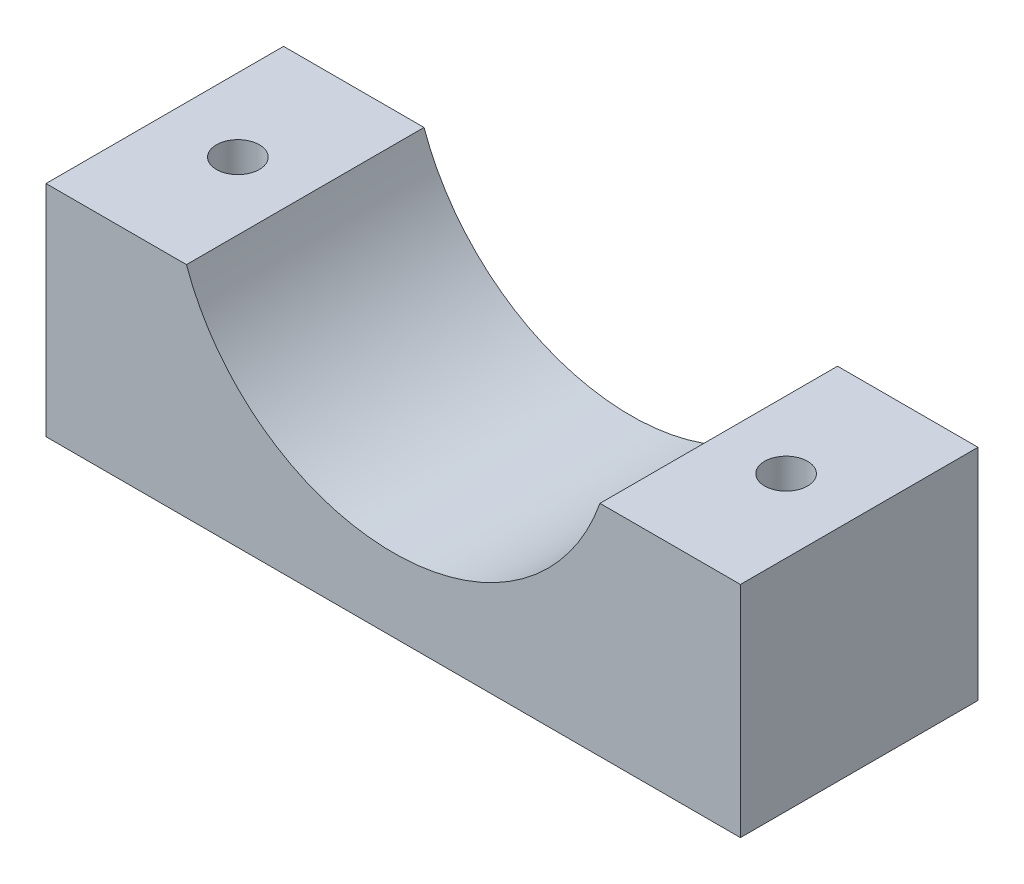
SolidWorks part; units mm, degrees
ref_plane "Front Plane" through (0, 0, 0) normal (0, 0, 1) x (1, 0, 0)
ref_plane "Top Plane" through (0, 0, 0) normal (0, 1, 0) x (1, 0, 0)
ref_plane "Right Plane" through (0, 0, 0) normal (1, 0, 0) x (0, 0, -1)
sketch "Sketch1" plane through (0, 0, 0) normal (0, 1, 0) x (1, 0, 0)
  line L1 (0, 0) -> (38, 0)
  line L2 (0, 0) -> (0, 13)
  line L3 (0, 13) -> (38, 13)
  line L4 (38, 0) -> (38, 13)
  dimension "D1" = 38
  dimension "D2" = 13
extrude "Boss-Extrude1" add sketch "Sketch1" along normal blind 12
sketch "Sketch2" plane through (0, 0, 0) normal (0, 0, 1) x (1, 0, 0)
  line L0 (0, 0) -> (38, 0) construction
  line L1 (0, 0) -> (38, 0) construction
  line L2 (0, 12) -> (0, 0) construction
  circle A0 centre (19, 16) radius 12
  dimension "D1" = 24
  dimension "D2" = 16
  dimension "D3" = 19
extrude "Cut-Extrude1" cut sketch "Sketch2" against normal up to surface (13 mm away) up to face at (19, 6, -13)
hole_wizard "Hole1" positions "Sketch3" profile "Sketch4" legacy
sketch "Sketch3" plane through (0, 0, 0) normal (0, -1, 0) x (-1, 0, 0)
  line L0 (-38, 0) -> (-38, 13) construction
  line L1 (0, 13) -> (0, 0) construction
  line L2 (0, 0) -> (-38, 0) construction
  point P0 (-34, 6.5)
  point P3 (-4, 6.5)
  dimension "D1" = 4
  dimension "D2" = 4
  dimension "D3" = 6.5
  dimension "D4" = 6.5
sketch "Sketch4" plane through (34, 0, -6.5) normal (1, 0, 0) x (0, 0, -1)
  line L0 (0, 0) -> (0, 12)
  line L1 (0, 12) -> (1.175, 12)
  line L2 (1.175, 12) -> (1.175, 0)
  line L3 (1.175, 0) -> (0, 0)
  line L4 (0, 110) -> (0, -10) construction
  dimension "Diameter" = 2.35
  dimension "Depth" = 12
